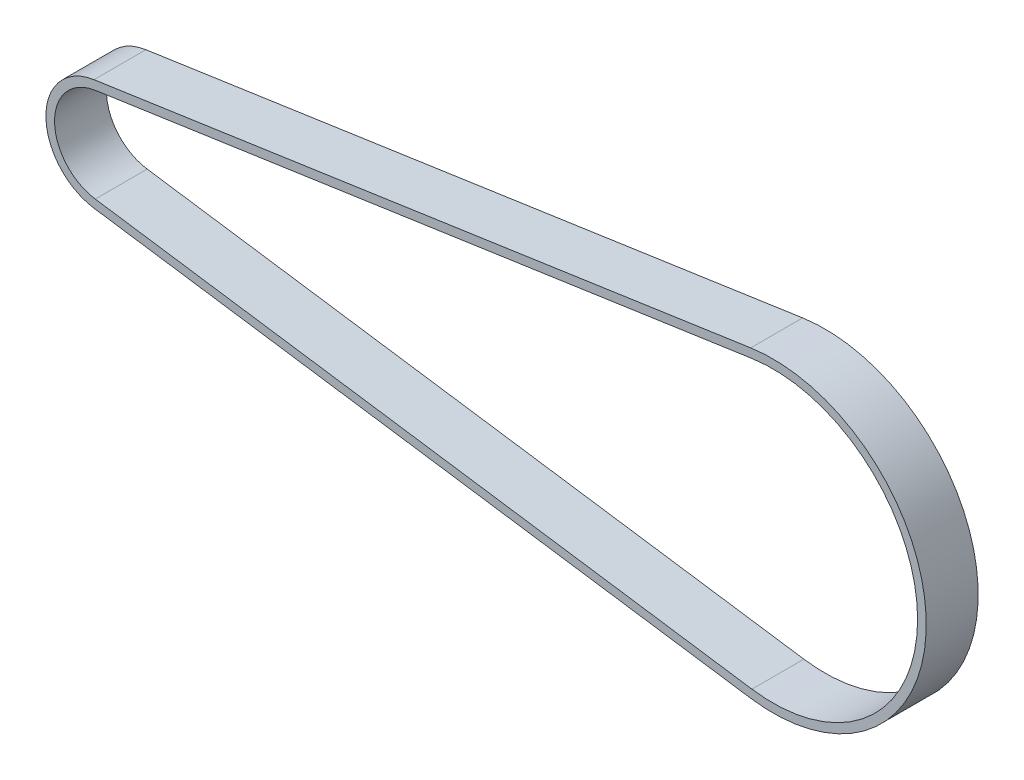
SolidWorks part; units mm, degrees
material "HYPALON"
ref_plane "Alzado" through (0, 0, 0) normal (0, 0, 1) x (1, 0, 0)
ref_plane "Planta" through (0, 0, 0) normal (0, 1, 0) x (1, 0, 0)
ref_plane "Vista lateral" through (0, 0, 0) normal (1, 0, 0) x (0, 0, -1)
sketch "Croquis1" plane through (0, 0, 0) normal (0, 0, 1) x (1, 0, 0)
  line L0 (-0.7963, 5.4421) -> (75.0794, 16.5439)
  line L1 (-0.7963, -5.4421) -> (75.0794, -16.5439)
  line L2 (-0.941, 6.4315) -> (74.9346, 17.5333)
  line L3 (-0.941, -6.4315) -> (74.9346, -17.5333)
  arc A0 (-0.7963, 5.4421) -> (-0.7963, -5.4421) centre (0, 0) ccw
  arc A1 (75.0794, -16.5439) -> (75.0794, 16.5439) centre (77.5, 0) ccw
  arc A2 (74.9346, -17.5333) -> (74.9346, 17.5333) centre (77.5, 0) ccw
  arc A3 (-0.941, 6.4315) -> (-0.941, -6.4315) centre (0, 0) ccw
  dimension "D1" = 11
  dimension "D2" = 33.44
  dimension "D3" = 77.5
  dimension "D4" = 1
extrude "Saliente-Extruir1" add sketch "Croquis1" along normal blind 6
